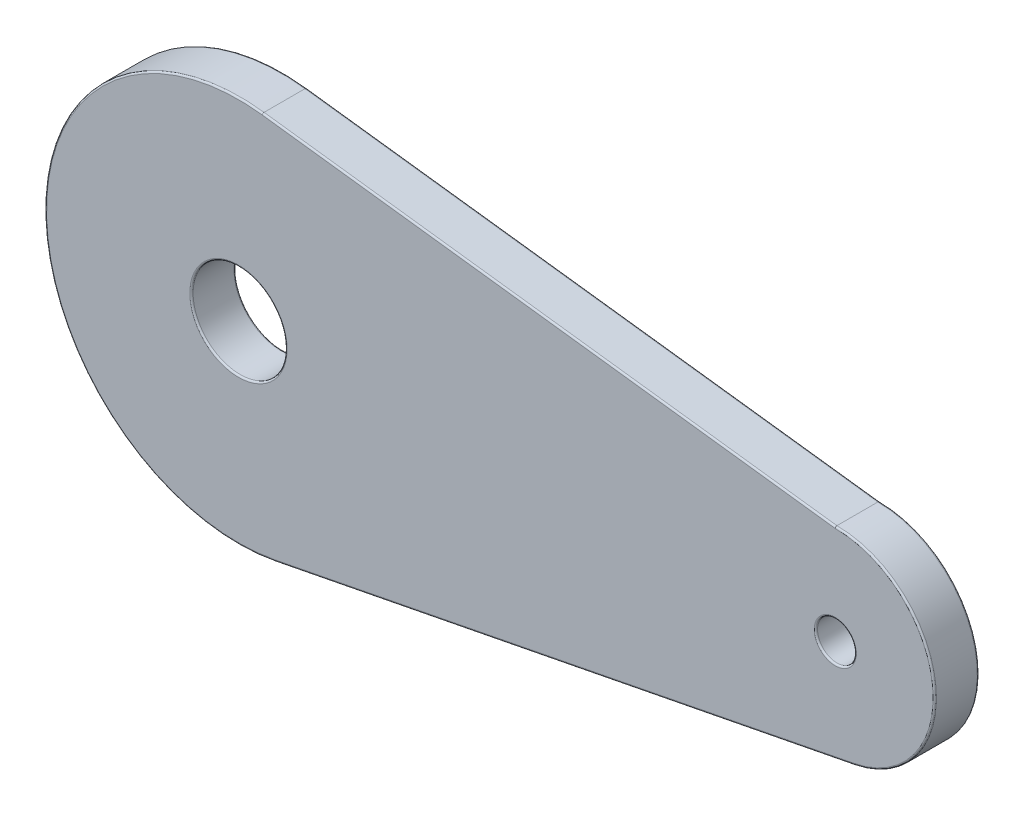
SolidWorks part; units mm, degrees
ref_plane "前视基准面" through (0, 0, 0) normal (0, 0, 1) x (1, 0, 0)
ref_plane "上视基准面" through (0, 0, 0) normal (0, 1, 0) x (1, 0, 0)
ref_plane "右视基准面" through (0, 0, 0) normal (1, 0, 0) x (0, 0, -1)
sketch "草图2" plane through (0, 0, 0) normal (0, 0, 1) x (1, 0, 0)
  line L0 (-20.22, 57.58) -> (33.7467, 59.4755) construction
  line L1 (-20.22, 57.58) -> (33.7467, 59.4755) construction
  line L2 (-18.0511, 74.9451) -> (33.7467, 68.4755)
  line L3 (-16.8604, 40.4055) -> (35.4745, 50.6429)
  circle A0 centre (-20.22, 57.58) radius 17.5 construction
  circle A1 centre (-20.22, 57.58) radius 17.5 construction
  circle A2 centre (33.7467, 59.4755) radius 9 construction
  arc A3 (-18.0511, 74.9451) -> (-16.8604, 40.4055) centre (-20.22, 57.58) ccw
  arc A4 (33.7467, 68.4755) -> (35.4745, 50.6429) centre (33.7467, 59.4755) cw
  circle A5 centre (-20.22, 57.58) radius 4.25
  circle A6 centre (33.7467, 59.4755) radius 1.75
  dimension "D1" = 18
  dimension "D2" = 3.5
  dimension "D3" = 8.5
extrude "凸台-拉伸1" add sketch "草图2" against normal blind 4
fillet "圆角1" radius 0.15 12 edges at (9.307, 45.5242, -4) (42.7048, 60.3434, -4) (7.8478, 71.7103, -4) (-37.7096, 56.9771, -4) (-15.97, 57.58, -4) (35.4967, 59.4755, -4) (7.8478, 71.7103, 0) (42.7048, 60.3434, 0) (9.307, 45.5242, 0) (-37.7096, 56.9771, 0) (-15.97, 57.58, 0) (35.4967, 59.4755, 0)
